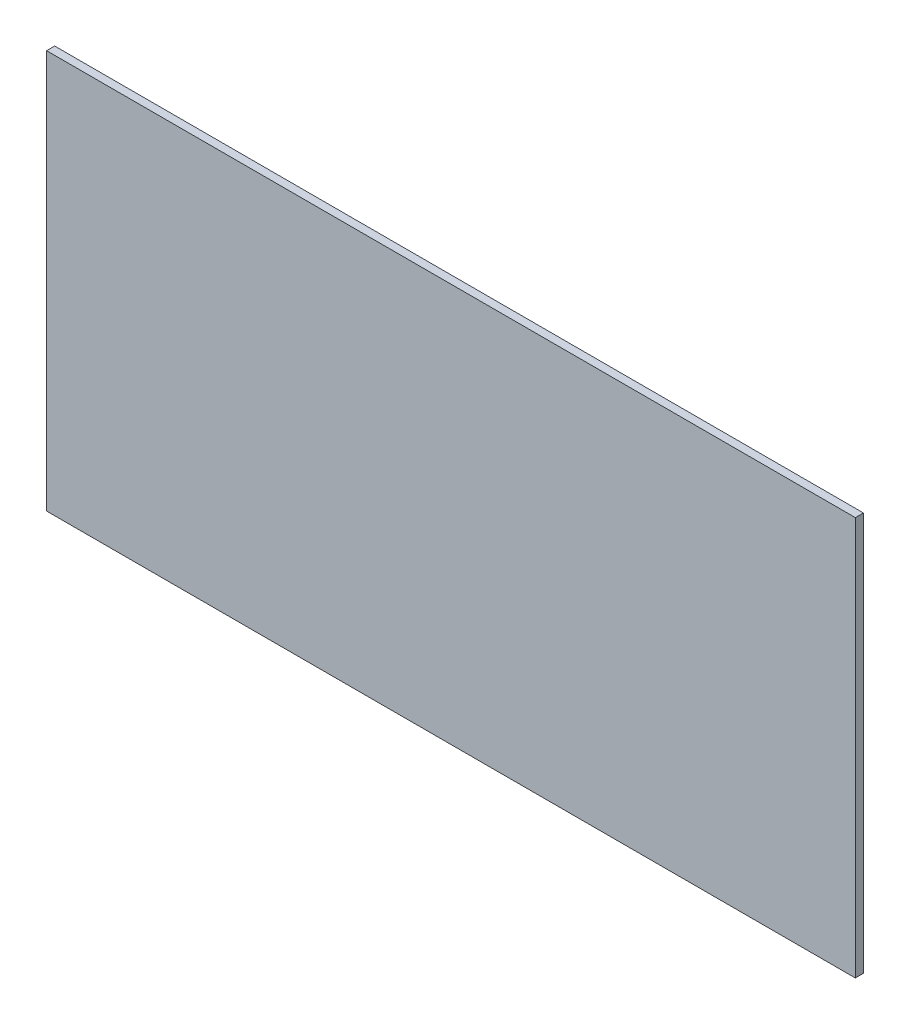
SolidWorks part; units mm, degrees
material "Custom Plastic"
ref_plane "X-Y Datum" through (0, 0, 0) normal (0, 0, 1) x (1, 0, 0)
ref_plane "X-Z Datum" through (0, 0, 0) normal (0, 1, 0) x (1, 0, 0)
ref_plane "Y-Z Datum" through (0, 0, 0) normal (1, 0, 0) x (0, 0, -1)
sketch "Sketch1" plane through (0, 0, 0) normal (0, 0, 1) x (1, 0, 0)
  line L0 (-158.775, 78.275) -> (-158.775, -78.275)
  line L1 (-148.775, 68.275) -> (148.775, 68.275)
  line L2 (-148.775, 68.275) -> (-148.775, -68.275)
  line L3 (-148.775, -68.275) -> (148.775, -68.275)
  line L4 (148.775, 68.275) -> (148.775, -68.275)
  line L5 (-148.775, 68.275) -> (148.775, -68.275) construction
  line L6 (-148.775, -68.275) -> (148.775, 68.275) construction
  line L7 (-158.775, -78.275) -> (158.775, -78.275)
  line L8 (158.775, 78.275) -> (158.775, -78.275)
  line L9 (-158.775, 78.275) -> (158.775, 78.275)
  circle A0 centre (-138, -57.5) radius 10.775
  circle A1 centre (-114, -57.5) radius 10.775 construction
  circle A2 centre (-126, -34.5) radius 10.775
  point P0 (0, 0)
  dimension "D1" = 21.55
  dimension "D2" = 24
  dimension "D3" = 23
  dimension "D4" = 12
  dimension "D5" = 136.55
  dimension "D6" = 297.55
  dimension "D7" = 10
extrude "Boss-Extrude1" add sketch "Sketch1" along normal blind 3.175 contours A0 L3 L4 L1 L2 A2 | A2 | A0 | A0 L2 L3 | L9 L0 L7 L8 L1 L4 L3 L2
